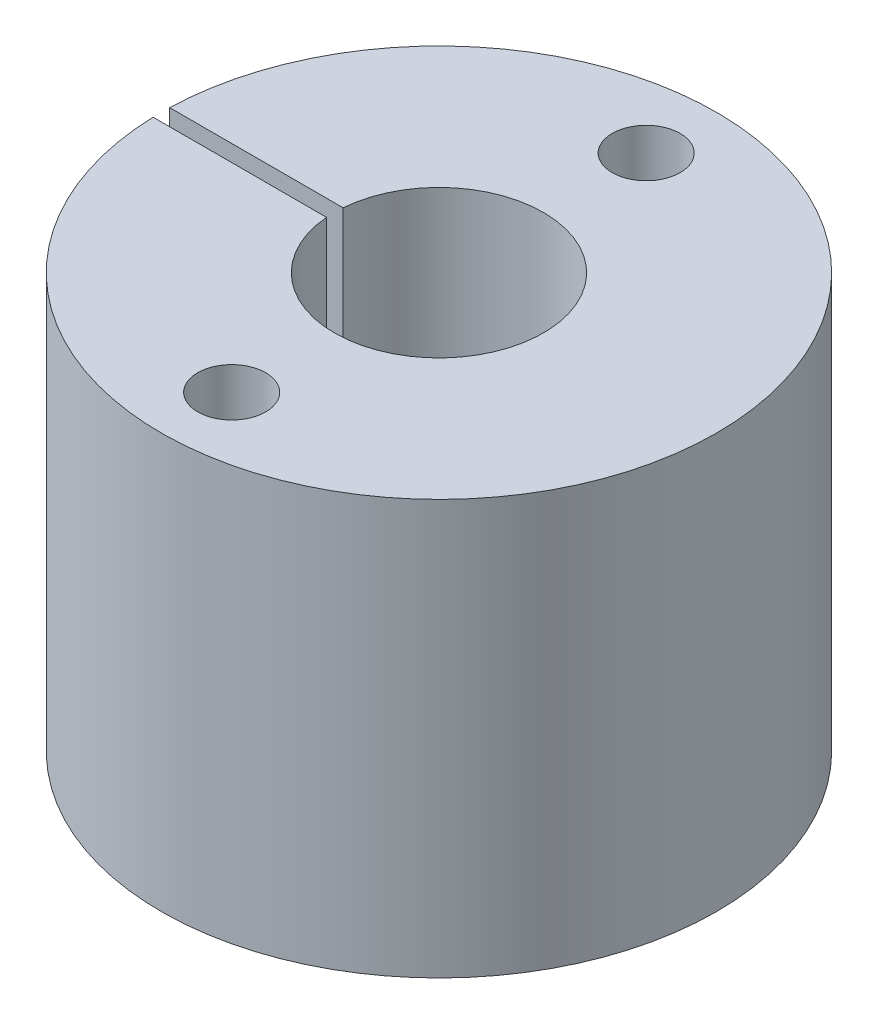
SolidWorks part; units mm, degrees
ref_plane "Front Plane" through (0, 0, 0) normal (0, 0, 1) x (1, 0, 0)
ref_plane "Top Plane" through (0, 0, 0) normal (0, 1, 0) x (1, 0, 0)
ref_plane "Right Plane" through (0, 0, 0) normal (1, 0, 0) x (0, 0, -1)
sketch "Sketch2" plane through (0, 0, 0) normal (0, 1, 0) x (1, 0, 0)
  line L0 (-12.6, 0) -> (-33.5, 0) construction
  line L1 (-12.5603, -1) -> (-33.4851, -1)
  line L2 (-33.4851, 1) -> (-12.5603, 1)
  circle A2 centre (0, 0) radius 33.5
  circle A3 centre (0, 0) radius 12.6
  dimension "D1" = 67
  dimension "D2" = 25.2
  dimension "D3" = 1
  dimension "D4" = 1
extrude "Boss-Extrude2" add sketch "Sketch2" along normal blind 50
sketch "Sketch3" plane through (0, 0, 0) normal (0, -1, 0) x (1, 0, 0)
  line L0 (0, -25) -> (0, 25) construction
  circle A0 centre (0, 25) radius 4.1
  circle A1 centre (0, -25) radius 4.1
  point P4 (0, 0)
  dimension "D2" = 8.2
  dimension "D3" = 8.2
  dimension "D1" = 25
extrude "Cut-Extrude1" cut sketch "Sketch3" against normal up to next
sketch "Sketch8" plane through (0, 0, 0) normal (0, -1, 0) x (1, 0, 0)
  line L1 (6.6184, 21.2216) -> (6.5814, 28.8425)
  line L2 (6.5814, 28.8425) -> (-0.037, 32.6209)
  line L3 (-0.037, 32.6209) -> (-6.6184, 28.7784)
  line L4 (-6.6184, 28.7784) -> (-6.5814, 21.1575)
  line L5 (-6.5814, 21.1575) -> (0.037, 17.3791)
  line L6 (0.037, 17.3791) -> (6.6184, 21.2216)
  line L7 (6.6184, -28.7784) -> (6.5814, -21.1575)
  line L8 (6.5814, -21.1575) -> (-0.037, -17.3791)
  line L9 (-0.037, -17.3791) -> (-6.6184, -21.2216)
  line L10 (-6.6184, -21.2216) -> (-6.5814, -28.8425)
  line L11 (-6.5814, -28.8425) -> (0.037, -32.6209)
  line L12 (0.037, -32.6209) -> (6.6184, -28.7784)
  circle A0 centre (0, 25) radius 6.6 construction
  circle A1 centre (0, -25) radius 6.6 construction
  dimension "D1" = 13.2
  dimension "D2" = 13.2
extrude "Cut-Extrude2" cut sketch "Sketch8" against normal blind 30
